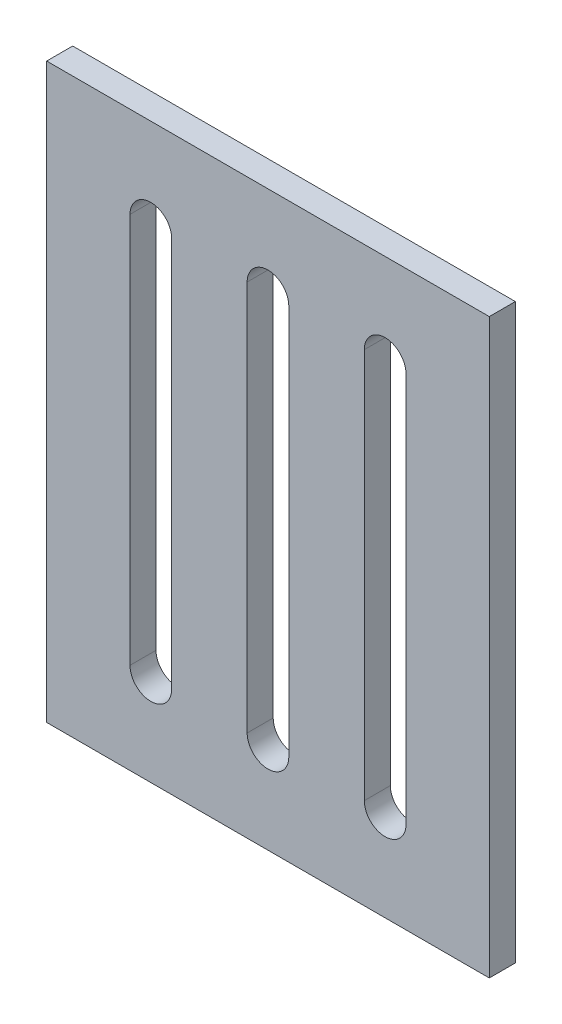
SolidWorks part; units mm, degrees
ref_plane "Front Plane" through (0, 0, 0) normal (0, 0, 1) x (1, 0, 0)
ref_plane "Top Plane" through (0, 0, 0) normal (0, 1, 0) x (1, 0, 0)
ref_plane "Right Plane" through (0, 0, 0) normal (1, 0, 0) x (0, 0, -1)
sketch "Sketch3" plane through (0, 0, 0) normal (0, 0, 1) x (1, 0, 0)
  line L0 (-85, 0) -> (85, 0) construction
  line L1 (-85, 110) -> (85, 110)
  line L2 (-85, 110) -> (-85, -110)
  line L3 (-85, -110) -> (85, -110)
  line L4 (85, 110) -> (85, -110)
  line L5 (-85, 110) -> (85, -110) construction
  line L6 (-85, -110) -> (85, 110) construction
  line L7 (0, 110) -> (0, -110) construction
  line L8 (0, 75) -> (0, -75) construction
  line L9 (8, 75) -> (8, -75)
  line L10 (-8, 75) -> (-8, -75)
  line L11 (-45, 75) -> (-45, -75) construction
  line L12 (-37, 75) -> (-37, -75)
  line L13 (-53, 75) -> (-53, -75)
  line L14 (45, 75) -> (45, -75) construction
  line L15 (37, 75) -> (37, -75)
  line L16 (53, 75) -> (53, -75)
  arc A4 (8, 75) -> (-8, 75) centre (0, 75) ccw
  arc A5 (-8, -75) -> (8, -75) centre (0, -75) ccw
  arc A6 (-37, 75) -> (-53, 75) centre (-45, 75) ccw
  arc A7 (-53, -75) -> (-37, -75) centre (-45, -75) ccw
  arc A8 (37, 75) -> (53, 75) centre (45, 75) cw
  arc A9 (53, -75) -> (37, -75) centre (45, -75) cw
  point P0 (0, 0)
  point P12 (-45, 0)
  point P20 (0, 0)
  point P26 (45, 0)
  dimension "D3" = 16
  dimension "D4" = 35
  dimension "D5" = 35
  dimension "D7" = 40
  dimension "D1" = 220
  dimension "D2" = 170
  dimension "D6" = 16
extrude "Boss-Extrude1" add sketch "Sketch3" along normal mid plane 10
